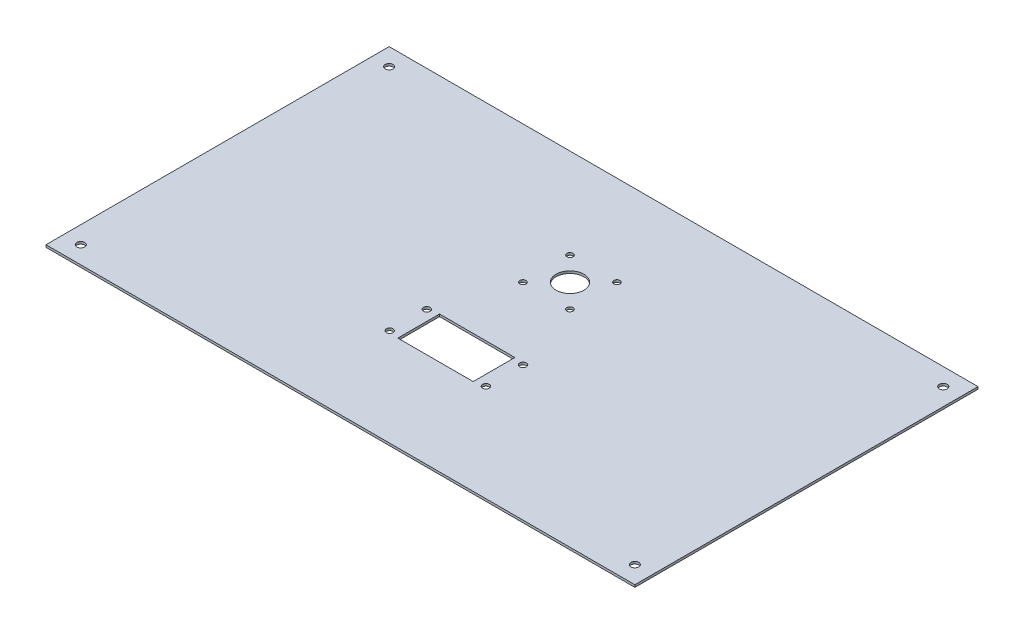
SolidWorks part; units mm, degrees
material "6061 Alloy"
ref_plane "Front Plane" through (0, 0, 0) normal (0, 0, 1) x (1, 0, 0)
ref_plane "Top Plane" through (0, 0, 0) normal (0, 1, 0) x (1, 0, 0)
ref_plane "Right Plane" through (0, 0, 0) normal (1, 0, 0) x (0, 0, -1)
sketch "Sketch1" plane through (0, 0, 0) normal (0, 1, 0) x (1, 0, 0)
  line L1 (-254, -148) -> (254, -148)
  line L2 (-254, -148) -> (-254, 148)
  line L3 (-254, 148) -> (254, 148)
  line L4 (254, -148) -> (254, 148)
  line L5 (-254, -148) -> (254, 148) construction
  line L6 (-254, 148) -> (254, -148) construction
  point P0 (0, 0)
  dimension "D1" = 508
  dimension "D2" = 296
extrude "Boss-Extrude1" add sketch "Sketch1" along normal blind 2
sketch "Sketch2" plane through (0, 2, 0) normal (0, 1, 0) x (1, 0, 0)
  line L0 (-20.28, 50) -> (-20.28, 70.28) construction
  line L1 (-20.28, 70.28) -> (0, 70.28) construction
  line L2 (0, 50) -> (0, 70.28) construction
  line L3 (0, 50) -> (-20.28, 50) construction
  line L4 (-15.5122, -30) -> (19.1586, -30) construction
  line L5 (0, 0) -> (0, 50) construction
  line L6 (254, 148) -> (-254, 148) construction
  line L7 (-32.5, -30) -> (32.5, -66) construction
  line L8 (32.5, -30) -> (-32.5, -30)
  line L9 (32.5, -30) -> (32.5, -66)
  line L10 (32.5, -66) -> (-32.5, -66)
  line L11 (-32.5, -30) -> (-32.5, -66)
  line L12 (32.5, -30) -> (-32.5, -66) construction
  line L14 (-41.5, -64) -> (41.5, -64) construction
  line L15 (-41.5, -64) -> (-41.5, -32) construction
  line L16 (-41.5, -32) -> (41.5, -32) construction
  line L17 (41.5, -64) -> (41.5, -32) construction
  line L18 (-41.5, -64) -> (41.5, -32) construction
  line L19 (-41.5, -32) -> (41.5, -64) construction
  circle A0 centre (0, 50) radius 12
  circle A1 centre (0, 50) radius 20.28 construction
  circle A2 centre (-20.28, 70.28) radius 2.65
  circle A3 centre (-20.28, 29.72) radius 2.65
  circle A4 centre (20.28, 29.72) radius 2.65
  circle A5 centre (20.28, 70.28) radius 2.65
  circle A6 centre (41.5, -32) radius 2.9
  circle A7 centre (41.5, -64) radius 2.9
  circle A8 centre (-41.5, -64) radius 2.9
  circle A9 centre (-41.5, -32) radius 2.9
  point P23 (0, -30)
  point P24 (0, -48)
  point P26 (0, -48)
  dimension "D1" = 24
  dimension "D2" = 40.56
  dimension "D3" = 5.3
  dimension "D9" = 5.8
  dimension "D4" = 98
  dimension "D5" = 32
  dimension "D6" = 65
  dimension "D7" = 36
  dimension "D8" = 83
  dimension "D10" = 30
extrude "Cut-Extrude1" cut sketch "Sketch2" against normal blind 10
sketch "Sketch4" plane through (0, 0, 0) normal (0, -1, 0) x (1, 0, 0)
  line L0 (-239, 148) -> (-239, 133) construction
  line L1 (-254, 148) -> (254, 148) construction
  line L2 (-239, 133) -> (-254, 133) construction
  line L3 (-254, -148) -> (-254, 148) construction
  line L4 (0, 148) -> (0, 0) construction
  line L5 (0, 0) -> (254, 0) construction
  line L6 (254, 148) -> (254, -148) construction
  circle A0 centre (-239, 133) radius 3.4
  circle A1 centre (239, 133) radius 3.4
  circle A2 centre (-239, -133) radius 3.4
  circle A3 centre (239, -133) radius 3.4
  dimension "D3" = 6.8
  dimension "D1" = 15
  dimension "D2" = 15
extrude "Cut-Extrude2" cut sketch "Sketch4" against normal blind 10
